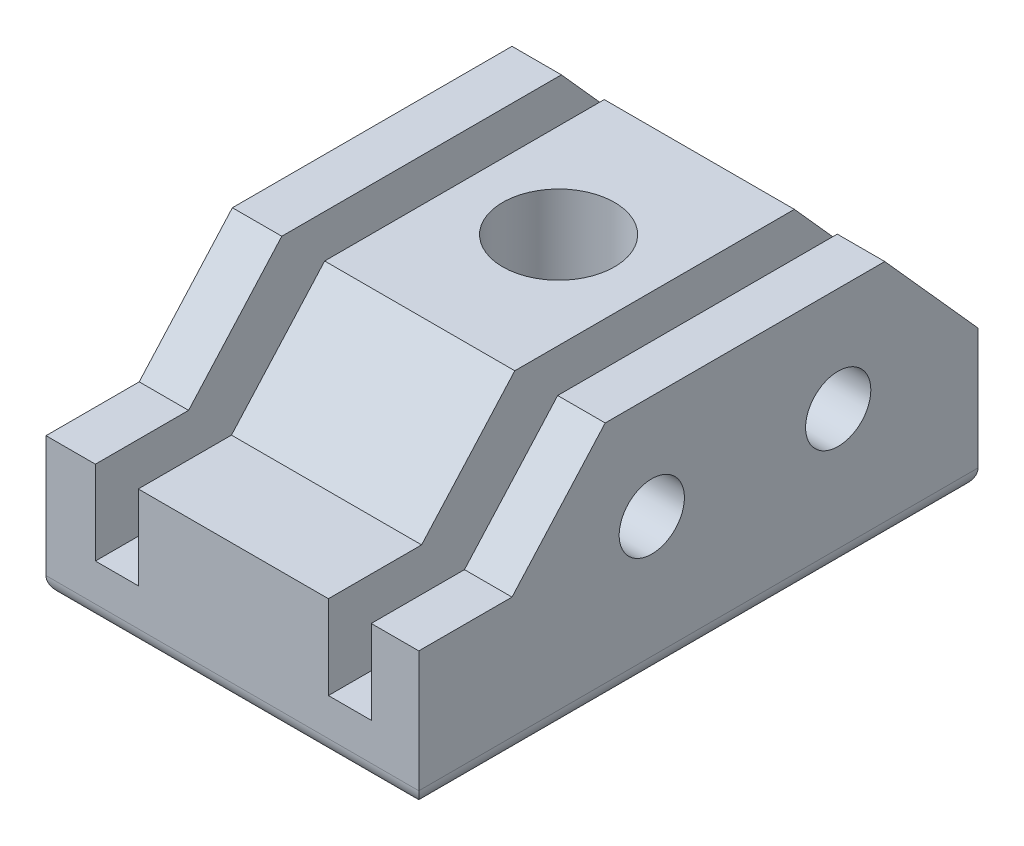
SolidWorks part; units mm, degrees
ref_plane "Front Plane" through (0, 0, 0) normal (0, 0, 1) x (1, 0, 0)
ref_plane "Top Plane" through (0, 0, 0) normal (0, 1, 0) x (1, 0, 0)
ref_plane "Right Plane" through (0, 0, 0) normal (1, 0, 0) x (0, 0, -1)
sketch "Sketch1" plane through (0, 0, 0) normal (1, 0, 0) x (0, 0, -1)
  line L1 (0, 0) -> (63.5, 0)
  line L2 (0, 0) -> (0, 6.35)
  line L3 (0, 6.35) -> (63.5, 6.35)
  line L4 (63.5, 0) -> (63.5, 6.35)
  dimension "D1" = 6.35
  dimension "D2" = 63.5
extrude "Boss-Extrude1" add sketch "Sketch1" against normal blind 50.8
sketch "Sketch2" plane through (0, 0, 0) normal (1, 0, 0) x (0, 0, -1)
  line L0 (0, 6.35) -> (0, 19.05)
  line L1 (0, 19.05) -> (12.7, 33.249)
  line L2 (12.7, 33.249) -> (50.8, 33.249)
  line L3 (50.8, 33.249) -> (63.5, 19.05)
  line L4 (63.5, 19.05) -> (63.5, 6.35)
  line L5 (63.5, 6.35) -> (0, 6.35)
  point P7 (31.75, 33.249)
  point P10 (31.75, 6.35)
  dimension "D1" = 38.1
  dimension "D2" = 12.7
  dimension "D3" = 12.7
  dimension "D4" = 19.05
  dimension "D5" = 19.05
extrude "Boss-Extrude2" add sketch "Sketch2" against normal blind 50.8
sketch "Sketch10" plane through (0, 0, -63.5) normal (0, 0, -1) x (-1, 0, 0)
  line L0 (25.4, 0) -> (25.4, 33.249) construction
  line L1 (50.8, 33.249) -> (0, 33.249) construction
  line L3 (6.477, 7.62) -> (6.477, 33.249)
  line L4 (6.477, 33.249) -> (12.319, 33.249)
  line L5 (12.319, 7.62) -> (12.319, 33.249)
  line L6 (6.477, 7.62) -> (12.319, 7.62)
  line L8 (50.8, 0) -> (0, 0) construction
  point P11 (12.319, 7.62)
  dimension "D1" = 7.62
  dimension "D2" = 5.842
  dimension "D3" = 13.081
extrude "Cut-Extrude1" cut sketch "Sketch10" against normal through all
pattern_linear "LPattern3" count 2 spacing 31.75 along (-1, 0, 0) of "Cut-Extrude1"
sketch "Sketch11" plane through (0, 0, 0) normal (1, 0, 0) x (0, 0, -1)
  circle A0 centre (19.05, 19.05) radius 4.445
  circle A1 centre (19.05, 19.05) radius 7.9375 construction
  circle A2 centre (44.45, 19.05) radius 4.445
  circle A3 centre (44.45, 19.05) radius 7.9375 construction
  dimension "D1" = 8.89
  dimension "D3" = 15.875
  dimension "D6" = 15.875
  dimension "D2" = 6.35
  dimension "D5" = 6.35
extrude "Cut-Extrude2" cut sketch "Sketch11" against normal through all
sketch "Sketch14" plane through (0, 33.249, 0) normal (0, 1, 0) x (1, 0, 0)
  line L3 (-38.227, 12.7) -> (-38.227, 50.8) construction
  point P0 (-25.781, 31.75)
  point P4 (-38.227, 31.75)
  dimension "D1" = 12.446
sketch "Sketch17" plane through (0, 40.0201, -44.7438) normal (0, 0.6667, -0.7454) x (-1, 0, 0)
  line L0 (12.319, -28.1343) -> (12.319, -9.0843) construction
  line L1 (38.227, -9.0843) -> (12.319, -9.0843) construction
  point P0 (25.273, -18.6093)
  point P4 (12.319, -18.6093)
  point P7 (25.273, -9.0843)
sketch "Sketch18" plane through (0, 8.4667, 9.466) normal (0, 0.6667, 0.7454) x (1, 0, 0)
  line L0 (-12.319, 33.249) -> (-12.319, 14.199) construction
  line L1 (-38.227, 33.249) -> (-12.319, 33.249) construction
  point P0 (-25.273, 23.724)
  point P1 (-25.273, 23.724)
  point P4 (-12.319, 23.724)
  point P7 (-25.273, 33.249)
ref_plane "Plane2" through (0, 33.02, 0) normal (0, -1, 0) x (-1, 0, 0)
sketch "Sketch22" plane through (0, 0, 0) normal (0, 0, 1) x (1, 0, 0)
  line L0 (-50.8, 19.05) -> (-50.8, 0) construction
  line L1 (0, 0) -> (-50.8, 0)
  line L2 (0, 0) -> (0, 7.62)
  line L3 (-6.477, 7.62) -> (-12.319, 7.62)
  line L4 (-50.8, 0) -> (-50.8, 7.62)
  line L5 (-38.227, 7.62) -> (-38.227, 19.05)
  line L6 (-38.227, 19.05) -> (-12.319, 19.05)
  line L7 (-12.319, 19.05) -> (-12.319, 7.62)
  line L8 (-38.227, 7.62) -> (-44.069, 7.62)
  line L9 (-50.8, 7.62) -> (-50.8, 19.05)
  line L10 (-50.8, 19.05) -> (-44.069, 19.05)
  line L11 (-44.069, 19.05) -> (-44.069, 7.62)
  line L12 (-6.477, 7.62) -> (-6.477, 19.05)
  line L13 (-6.477, 19.05) -> (0, 19.05)
  line L14 (0, 19.05) -> (0, 7.62)
extrude "Boss-Extrude3" add sketch "Sketch22" along normal blind 12.7
sketch "Sketch23" plane through (0, 33.249, 0) normal (0, 1, 0) x (1, 0, 0)
  line L0 (-25.4, 63.5) -> (-25.4, -12.7) construction
  line L1 (-50.8, 63.5) -> (0, 63.5) construction
  line L2 (-50.8, -12.7) -> (0, -12.7) construction
  circle A0 centre (-25.4, 31.75) radius 7.62
  point P15 (-34.579, 50.8)
  dimension "D1" = 15.24
extrude "Cut-Extrude6" cut sketch "Sketch23" against normal through all
fillet "Fillet2" radius 2.54 4 edges at (-25.4, 0, -63.5) (0, 0, -25.4) (-50.8, 0, -25.4) (-25.4, 0, 12.7)
sketch "Sketch24" plane through (0, 0, 0) normal (0, -1, 0) x (1, 0, 0)
  line L0 (-20.4, -46.15) -> (-30.4, -46.15) construction
  line L1 (-25.4, -60.96) -> (-25.4, 10.16) construction
  line L2 (-48.26, -60.96) -> (-2.54, -60.96) construction
  line L3 (-2.54, 10.16) -> (-48.26, 10.16) construction
  line L4 (-20.4, 3.35) -> (-30.4, 3.35) construction
  circle A1 centre (-30.4, -46.15) radius 3.175
  circle A2 centre (-20.4, -46.15) radius 3.175
  circle A3 centre (-20.4, 3.35) radius 3.175
  circle A4 centre (-30.4, 3.35) radius 3.175
  circle A5 centre (-25.4, -31.75) radius 7.62 construction
  point P3 (-25.4, -46.15)
  point P12 (-25.4, 3.35)
  dimension "D2" = 6.35
  dimension "D1" = 10
  dimension "D3" = 49.5
  dimension "D4" = 14.4
extrude "Cut-Extrude7" cut sketch "Sketch24" against normal blind 10
